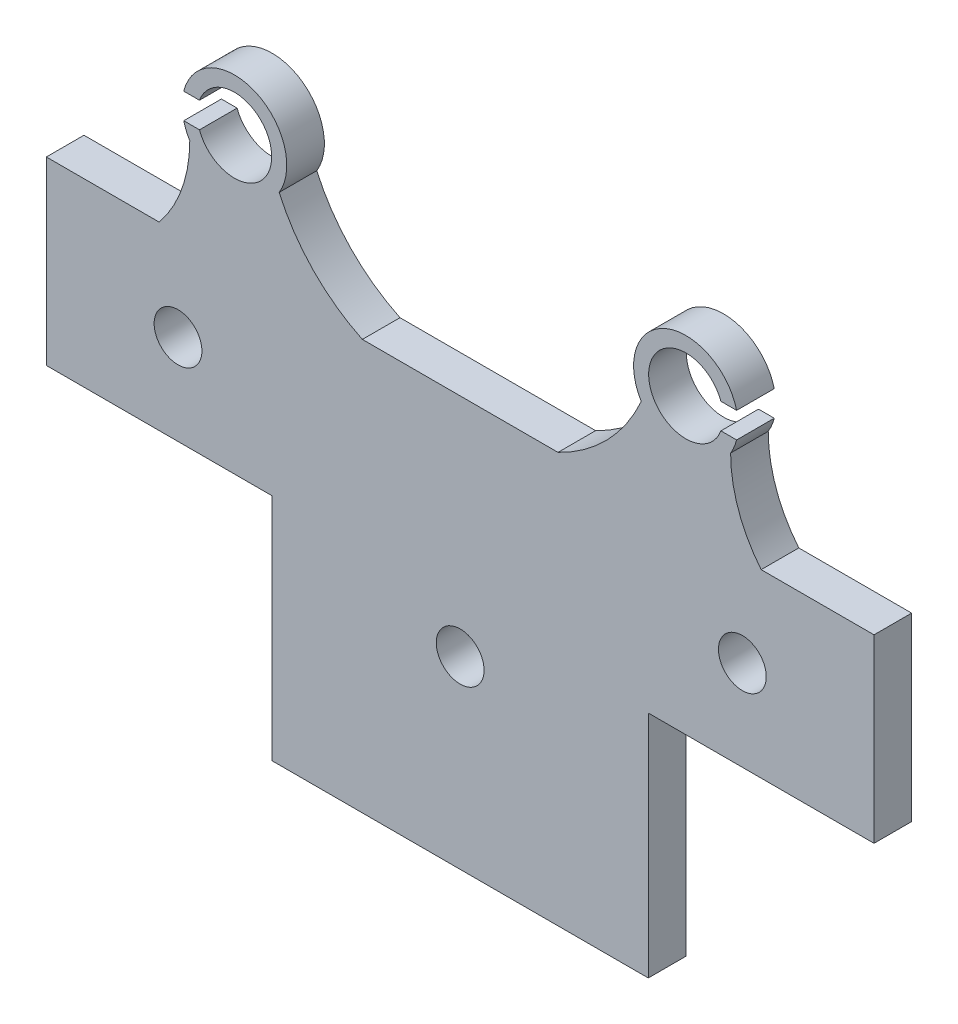
SolidWorks part; units mm, degrees
ref_plane "Alzado" through (0, 0, 0) normal (0, 0, 1) x (1, 0, 0)
ref_plane "Planta" through (0, 0, 0) normal (0, 1, 0) x (1, 0, 0)
ref_plane "Vista lateral" through (0, 0, 0) normal (1, 0, 0) x (0, 0, -1)
sketch "Croquis1" plane through (0, 0, 0) normal (0, 0, 1) x (1, 0, 0)
  line L0 (13, 0) -> (-13, 0)
  line L1 (-55, 0) -> (-55, -24)
  line L2 (-55, -24) -> (-25, -24)
  line L3 (-25, -24) -> (-25, -54.5)
  line L4 (-25, -54.5) -> (25, -54.5)
  line L5 (0, -54.5) -> (0, 0) construction
  line L6 (-40, 0) -> (-55, 0)
  line L7 (40, 0) -> (55, 0)
  line L8 (55, 0) -> (55, -24)
  line L9 (25, -24) -> (25, -54.5)
  line L10 (55, -24) -> (25, -24)
  circle A0 centre (-30, 15) radius 4.95
  arc A2 (-24.0615, 11.3894) -> (-35.9385, 11.3894) centre (-30, 15) ccw
  arc A3 (-35.9385, 11.3894) -> (-40, 0) centre (-53.9385, 11.3894) cw
  arc A4 (-24.0615, 11.3894) -> (-13, 0) centre (-3.0454, 20.7342) ccw
  circle A5 centre (-30, 15) radius 6.95 construction
  circle A7 centre (-37.5, -12) radius 3.175
  circle A8 centre (0, -30) radius 3.175
  arc A9 (24.0615, 11.3894) -> (13, 0) centre (3.0454, 20.7342) cw
  circle A10 centre (30, 15) radius 4.95
  arc A11 (24.0615, 11.3894) -> (35.9385, 11.3894) centre (30, 15) cw
  arc A12 (35.9385, 11.3894) -> (40, 0) centre (53.9385, 11.3894) ccw
  circle A13 centre (37.5, -12) radius 3.175
  dimension "D2" = 9.9
  dimension "D3" = 15
  dimension "D5" = 18
  dimension "D6" = 15
  dimension "D8" = 23
  dimension "D15" = 37.5
  dimension "D14" = 6.35
  dimension "D1" = 2
  dimension "D4" = 30
  dimension "D7" = 55
  dimension "D9" = 13
  dimension "D10" = 24
  dimension "D11" = 30
  dimension "D12" = 54.5
  dimension "D13" = 12
  dimension "D16" = 30
extrude "Saliente-Extruir1" add sketch "Croquis1" along normal blind 5
sketch "Croquis2" plane through (0, 0, 0) normal (0, 0, 1) x (1, 0, 0)
  line L0 (-30, 15) -> (-36.95, 15) construction
  line L1 (-30, 16.7) -> (-36.7389, 16.7)
  line L2 (-30, 13.3) -> (-36.7389, 13.3)
  line L3 (-30, 13.3) -> (-36.95, 13.3) construction
  line L4 (-30, 16.7) -> (-36.95, 16.7) construction
  line L5 (-30, 16.7) -> (-30, 13.3)
  line L6 (0, 0) -> (0, -26.825) construction
  line L7 (30, 16.7) -> (30, 13.3)
  line L8 (30, 13.3) -> (36.7389, 13.3)
  line L9 (30, 16.7) -> (36.7389, 16.7)
  arc A0 (-24.0615, 11.3894) -> (-35.9385, 11.3894) centre (-30, 15) ccw construction
  arc A1 (-36.7389, 16.7) -> (-36.7389, 13.3) centre (-30, 15) ccw
  circle A2 centre (0, -30) radius 3.175 construction
  arc A3 (36.7389, 16.7) -> (36.7389, 13.3) centre (30, 15) cw
  dimension "D1" = 1.7
  dimension "D2" = 1.7
extrude "Cortar-Extruir1" cut sketch "Croquis2" along normal through all
